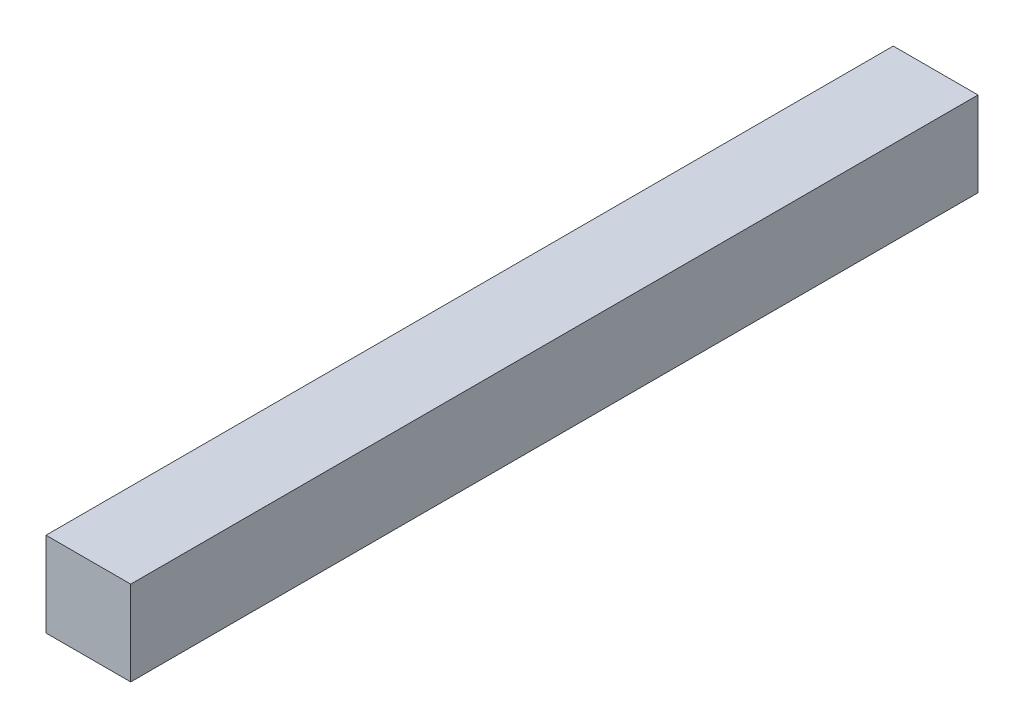
SolidWorks part; units mm, degrees
ref_plane "前视基准面" through (0, 0, 0) normal (0, 0, 1) x (1, 0, 0)
ref_plane "上视基准面" through (0, 0, 0) normal (0, 1, 0) x (1, 0, 0)
ref_plane "右视基准面" through (0, 0, 0) normal (1, 0, 0) x (0, 0, -1)
sketch "草图1" plane through (0, 0, 0) normal (0, 0, 1) x (1, 0, 0)
  line L1 (-15, 15) -> (15, 15)
  line L2 (-15, 15) -> (-15, -15)
  line L3 (-15, -15) -> (15, -15)
  line L4 (15, 15) -> (15, -15)
  line L5 (-15, 15) -> (15, -15) construction
  line L6 (-15, -15) -> (15, 15) construction
  point P0 (0, 0)
  dimension "D1" = 30
  dimension "D2" = 30
extrude "凸台-拉伸1" add sketch "草图1" along normal mid plane 300
